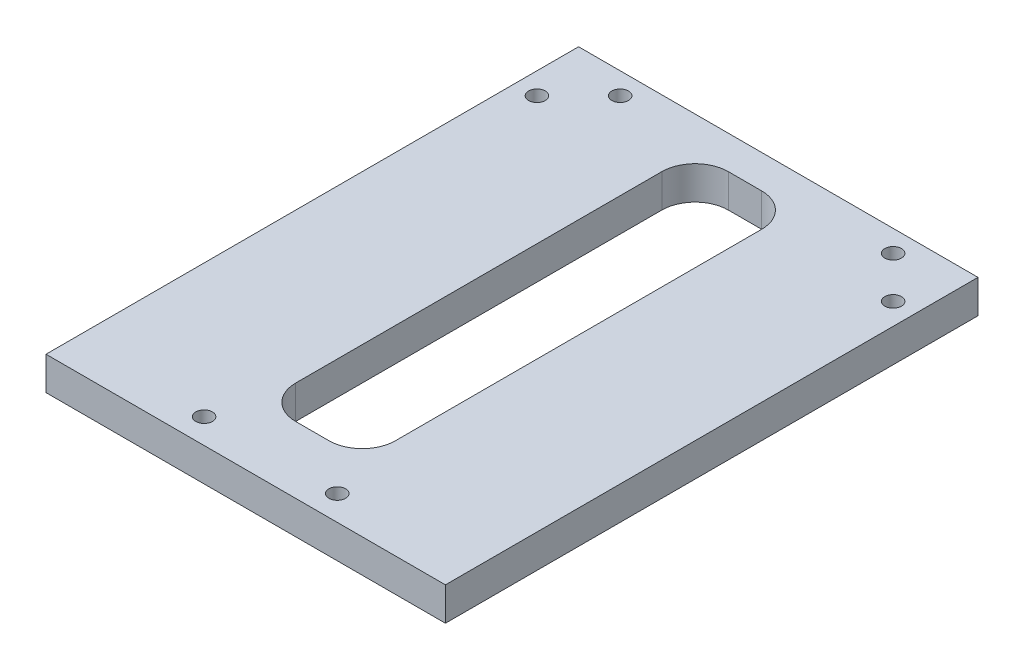
SolidWorks part; units mm, degrees
ref_plane "Front Plane" through (0, 0, 0) normal (0, 0, 1) x (1, 0, 0)
ref_plane "Top Plane" through (0, 0, 0) normal (0, 1, 0) x (1, 0, 0)
ref_plane "Right Plane" through (0, 0, 0) normal (1, 0, 0) x (0, 0, -1)
sketch "Sketch1" plane through (0, 0, 0) normal (0, 1, 0) x (1, 0, 0)
  line L0 (60, 160) -> (60, 150)
  line L1 (0, 0) -> (120, 0)
  line L2 (0, 0) -> (0, 160)
  line L3 (0, 160) -> (120, 160)
  line L4 (120, 0) -> (120, 160)
  line L5 (120, 80) -> (75, 80)
  line L6 (0, 80) -> (45, 80)
  line L7 (60, 0) -> (60, 20)
  line L8 (60, 150) -> (45, 150)
  line L10 (45, 150) -> (75, 150)
  line L11 (45, 150) -> (45, 20)
  line L12 (45, 20) -> (75, 20)
  line L13 (75, 150) -> (75, 20)
  dimension "D1" = 160
  dimension "D2" = 120
  dimension "D3" = 10
  dimension "D4" = 45
  dimension "D5" = 45
  dimension "D6" = 20
extrude "Boss-Extrude3" add sketch "Sketch1" along normal blind 10 contours L11 L8 L0 L3 L2 L6 | L10 L13 L5 L4 L3 L0 | L5 L13 L12 L7 L1 L4 | L12 L11 L6 L2 L1 L7
fillet "Fillet3" radius 10 4 edges at (45, 5, -20) (75, 5, -20) (75, 5, -150) (45, 5, -150)
sketch "Sketch2" plane through (0, 10, 0) normal (0, 1, 0) x (1, 0, 0)
  line L0 (120, 160) -> (112.5, 160)
  line L1 (0, 160) -> (120, 160) construction
  line L2 (112.5, 160) -> (101, 160)
  line L3 (120, 160) -> (120, 148.5)
  line L4 (120, 0) -> (120, 160) construction
  line L5 (112.5, 160) -> (112.5, 152.5)
  line L6 (101, 160) -> (101, 153.5)
  line L7 (0, 160) -> (7.5, 160)
  line L8 (120, 141) -> (113.5, 141)
  line L9 (7.5, 160) -> (19, 160)
  line L10 (7.5, 160) -> (7.5, 152.5)
  line L11 (19, 160) -> (19, 153.5)
  line L12 (0, 160) -> (0, 141)
  line L13 (0, 0) -> (0, 160) construction
  line L14 (0, 141) -> (6.5, 141)
  circle A0 centre (112.5, 152.5) radius 2.25
  circle A1 centre (101, 153.5) radius 5
  circle A2 centre (113.5, 141) radius 5
  circle A3 centre (19, 153.5) radius 2.5
  circle A4 centre (7.5, 152.5) radius 2.25
  circle A5 centre (6.5, 141) radius 2.5
  dimension "D5" = 4.5
  dimension "D7" = 10
  dimension "D3" = 10
  dimension "D12" = 5
  dimension "D13" = 4.5
  dimension "D16" = 5
  dimension "D1" = 7.5
  dimension "D2" = 11.5
  dimension "D4" = 7.5
  dimension "D6" = 6.5
  dimension "D8" = 7.5
  dimension "D9" = 11.5
  dimension "D10" = 7.5
  dimension "D11" = 6.5
  dimension "D14" = 19
  dimension "D15" = 6.5
extrude "Cut-Extrude1" cut sketch "Sketch2" against normal blind 100
sketch "Sketch3" plane through (0, 10, 0) normal (0, 1, 0) x (1, 0, 0)
  line L0 (120, 160) -> (101, 160)
  line L1 (0, 160) -> (120, 160) construction
  line L2 (101, 160) -> (101, 153.5)
  line L3 (120, 160) -> (120, 141)
  line L4 (120, 0) -> (120, 160) construction
  line L5 (120, 141) -> (113.5, 141)
  circle A1 centre (113.5, 141) radius 2.5
  circle A2 centre (101, 153.5) radius 2.5
  dimension "D5" = 5
  dimension "D6" = 5
  dimension "D1" = 19
  dimension "D2" = 6.5
  dimension "D3" = 19
  dimension "D4" = 6.5
extrude "Cut-Extrude3" cut sketch "Sketch3" against normal blind 100
sketch "Sketch4" plane through (0, 0, 0) normal (0, -1, 0) x (1, 0, 0)
  circle A0 centre (113.5, -141) radius 5
  circle A1 centre (101, -153.5) radius 5
  circle A2 centre (19, -153.5) radius 5
  circle A3 centre (6.5, -141) radius 5
  dimension "D1" = 10
  dimension "D2" = 10
  dimension "D3" = 10
  dimension "D4" = 10
extrude "Cut-Extrude4" cut sketch "Sketch4" against normal blind 5 contours A3 | A2 | A0 | A1
sketch "Sketch5" plane through (0, 0, 0) normal (0, -1, 0) x (1, 0, 0)
  line L0 (120, -160) -> (112.5, -160)
  line L2 (0, -160) -> (120, -160) construction
  line L3 (112.5, -160) -> (112.5, -152.5)
  line L4 (0, -149.2821) -> (7.8517, -149.2821)
  line L5 (0, 0) -> (0, -160) construction
  circle A0 centre (112.5, -152.5) radius 2.25
  dimension "D2" = 7.5
  dimension "D3" = 4.5
  dimension "D1" = 7.5
extrude "Cut-Extrude7" cut sketch "Sketch5" against normal blind 5 contours A0
sketch "Sketch8" plane through (0, 0, 0) normal (0, -1, 0) x (-1, 0, 0)
  line L0 (-112.5, 152.5) -> (-112.5, 160)
  line L1 (0, 160) -> (-120, 160) construction
  line L2 (-112.5, 160) -> (-120, 160)
  line L3 (0, 160) -> (-7.5, 160)
  line L4 (-7.5, 160) -> (-7.5, 152.5)
  circle A1 centre (-7.5, 153.623) radius 2.25
  dimension "D2" = 4.5
  dimension "D1" = 7.5
extrude "Cut-Extrude8" cut sketch "Sketch8" against normal blind 5
sketch "Sketch9" plane through (0, 0, 0) normal (0, -1, 0) x (-1, 0, 0)
  line L0 (0, 0) -> (-7.5, 0)
  line L1 (0, 0) -> (-120, 0) construction
  line L2 (-7.5, 0) -> (-7.5, 7.5)
  line L3 (-120, 0) -> (-120, 7.5)
  line L4 (-120, 0) -> (-120, 160) construction
  line L5 (-120, 7.5) -> (-112.5, 7.5)
  circle A0 centre (-7.5, 7.5) radius 2.25
  circle A1 centre (-112.5, 7.5) radius 2.25
  dimension "D3" = 4.5
  dimension "D5" = 4.5
  dimension "D1" = 7.5
  dimension "D2" = 7.5
  dimension "D4" = 7.5
extrude "Cut-Extrude9" cut sketch "Sketch9" against normal blind 5
sketch "Sketch10" plane through (0, 5, 0) normal (0, -1, 0) x (-1, 0, 0)
  line L0 (-112.5, 7.5) -> (-112.5, 0)
  line L1 (0, 0) -> (-120, 0) construction
  line L2 (-112.5, 0) -> (-80, 0)
  line L3 (-7.5, 7.5) -> (-7.5, 0)
  line L4 (-7.5, 0) -> (-40, 0)
  line L5 (-40, 0) -> (-80, 0)
  line L6 (-40, 0) -> (-40, 7.5)
  line L7 (-80, 0) -> (-80, 7.5)
  circle A0 centre (-80, 7.5) radius 5
  circle A1 centre (-40, 7.5) radius 5
  circle A3 centre (-80, 7.5) radius 2.5
  circle A4 centre (-40, 7.5) radius 2.5
  dimension "D5" = 10
  dimension "D6" = 10
  dimension "D7" = 5
  dimension "D8" = 5
  dimension "D1" = 32.5
  dimension "D2" = 32.5
  dimension "D3" = 40
  dimension "D4" = 7.5
extrude "Cut-Extrude13" cut sketch "Sketch10" along normal blind 12 contours A0 | A1
sketch "Sketch12" plane through (0, 5, 0) normal (0, -1, 0) x (-1, 0, 0)
  line L0 (-80, 7.5) -> (-80, -2.9337)
  line L1 (-40, 7.5) -> (-40, -4.391)
  circle A0 centre (-80, 7.5) radius 2.5
  circle A1 centre (-40, 7.5) radius 2.5
  dimension "D1" = 5
  dimension "D2" = 5
extrude "Cut-Extrude14" cut sketch "Sketch12" against normal blind 12 contours A1 | A0
